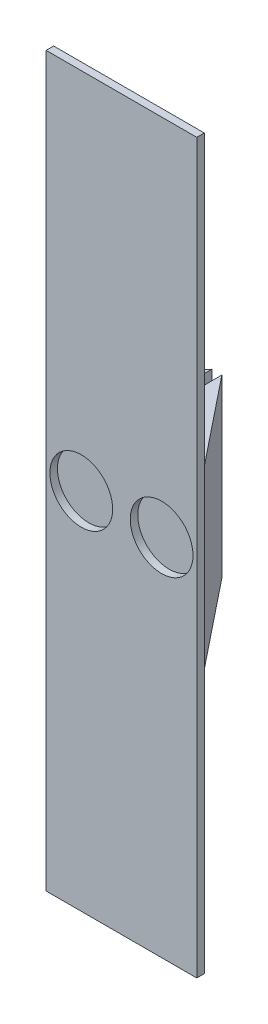
SolidWorks part; units mm, degrees
ref_plane "前视基准面" through (0, 0, 0) normal (0, 0, 1) x (1, 0, 0)
ref_plane "上视基准面" through (0, 0, 0) normal (0, 1, 0) x (1, 0, 0)
ref_plane "右视基准面" through (0, 0, 0) normal (1, 0, 0) x (0, 0, -1)
other "Configuration Table"
sketch "草图1" plane through (0, 0, 0) normal (0, 0, 1) x (1, 0, 0)
  line L1 (-15.6524, 41.5979) -> (44.3476, 41.5979)
  line L2 (-15.6524, 41.5979) -> (-15.6524, -18.4021)
  line L3 (-15.6524, -18.4021) -> (44.3476, -18.4021)
  line L4 (44.3476, 41.5979) -> (44.3476, -18.4021)
  dimension "D1" = 60
  dimension "D2" = 60
extrude "凸台-拉伸1" add sketch "草图1" along normal blind 3
sketch "草图2" plane through (0, 0, 0) normal (0, 0, -1) x (-1, 0, 0)
  line L0 (-44.3476, 41.5979) -> (-16.3476, 41.5979)
  line L1 (-44.3476, 41.5979) -> (15.6524, 41.5979) construction
  line L2 (-16.3476, 41.5979) -> (-16.3476, -18.4021)
  line L3 (15.6524, -18.4021) -> (-44.3476, -18.4021) construction
  line L4 (-16.3476, -18.4021) -> (-44.3476, -18.4021)
  line L5 (-44.3476, -18.4021) -> (-44.3476, 41.5979)
  line L6 (15.6524, 41.5979) -> (-12.3476, 41.5979)
  line L7 (-12.3476, 41.5979) -> (-12.3476, -18.4021)
  line L8 (-12.3476, -18.4021) -> (15.6524, -18.4021)
  line L9 (15.6524, -18.4021) -> (15.6524, 41.5979)
extrude "凸台-拉伸2" add sketch "草图2" along normal blind 35
sketch "草图3" plane through (0, 41.5979, 0) normal (0, 1, 0) x (1, 0, 0)
  line L0 (16.3476, 35) -> (44.3476, 0)
  line L1 (44.3476, -3) -> (44.3476, 35) construction
  line L2 (44.3476, 0) -> (44.3476, 35)
  line L3 (44.3476, 35) -> (16.3476, 35)
  line L5 (-15.6524, -3) -> (-15.6524, 35) construction
  line L7 (12.3476, 35) -> (-15.6524, 0)
  line L8 (-15.6524, 0) -> (-15.6524, 35)
  line L9 (-15.6524, 35) -> (12.3476, 35)
extrude "切除-拉伸1" cut sketch "草图3" against normal blind 60
sketch "草图4" plane through (0, 0, 3) normal (0, 0, 1) x (1, 0, 0)
  line L0 (-15.6524, 41.5979) -> (-14.1524, 41.5979)
  line L1 (44.3476, 41.5979) -> (-15.6524, 41.5979) construction
  line L2 (-14.1524, 41.5979) -> (10.8476, 41.5979)
  line L3 (10.8476, 41.5979) -> (10.8476, 11.5979)
  line L4 (10.8476, 11.5979) -> (-1.6524, 11.5979)
  line L5 (44.3476, 41.5979) -> (42.8476, 41.5979)
  line L6 (42.8476, 41.5979) -> (17.8476, 41.5979)
  line L7 (17.8476, 41.5979) -> (17.8476, 11.5979)
  line L8 (17.8476, 11.5979) -> (30.3476, 11.5979)
  circle A0 centre (-1.6524, 11.5979) radius 12.5
  circle A1 centre (30.3476, 11.5979) radius 12.5
extrude "切除-拉伸2" cut sketch "草图4" against normal blind 3
sketch "草图5" plane through (0, 41.5979, 0) normal (0, 1, 0) x (1, 0, 0)
  line L0 (12.3476, 35) -> (12.3476, 0)
  line L1 (12.3476, 0) -> (16.3476, 0)
  line L2 (16.3476, 0) -> (16.3476, 20)
  line L3 (16.3476, 35) -> (16.3476, 0) construction
  line L4 (16.3476, 20) -> (44.3476, 0)
  line L5 (44.3476, 0) -> (44.3476, -3)
  line L6 (44.3476, -3) -> (-15.6524, -3)
  line L7 (44.3476, -3) -> (-15.6524, -3) construction
  line L8 (-15.6524, -3) -> (-15.6524, 0)
  line L9 (-15.6524, 0) -> (12.3476, 35) construction
  line L10 (-15.6524, 0) -> (12.3476, 35)
extrude "凸台-拉伸3" add sketch "草图5" along normal blind 110
sketch "草图6" plane through (0, -18.4021, 0) normal (0, -1, 0) x (1, 0, 0)
  line L0 (-15.6524, 3) -> (-15.6524, 0)
  line L1 (-15.6524, 0) -> (12.3476, -35)
  line L2 (-15.6524, 0) -> (12.3476, -35) construction
  line L3 (12.3476, -35) -> (12.3476, 0)
  line L4 (12.3476, 0) -> (16.3476, 0)
  line L5 (16.3476, 0) -> (16.3476, -35)
  line L6 (16.3476, -35) -> (44.3476, 0)
  line L7 (16.3476, -35) -> (44.3476, 0) construction
  line L8 (44.3476, 0) -> (44.3476, 3)
  line L9 (44.3476, 3) -> (-15.6524, 3)
extrude "凸台-拉伸4" add sketch "草图6" along normal blind 110
sketch "草图7" plane through (0, -128.4021, 0) normal (0, -1, 0) x (1, 0, 0)
  line L0 (44.3476, 0) -> (16.3476, -35)
  line L1 (16.3476, 0) -> (16.3476, -35) construction
  line L2 (16.3476, -35) -> (44.3476, 0) construction
  line L3 (16.3476, -35) -> (16.3476, 0)
  line L4 (16.3476, 0) -> (44.3476, 0)
  line L5 (12.3476, -35) -> (-15.6524, 0)
  line L6 (-15.6524, 0) -> (12.3476, 0)
  line L7 (12.3476, -35) -> (12.3476, 0) construction
  line L8 (12.3476, 0) -> (12.3476, -35)
extrude "切除-拉伸3" cut sketch "草图7" against normal blind 100
sketch "草图9" plane through (0, 151.5979, 0) normal (0, 1, 0) x (1, 0, 0)
  line L0 (-15.6524, 0) -> (12.3476, 0)
  line L1 (12.3476, 0) -> (12.3476, 35)
  line L2 (12.3476, 35) -> (-15.6524, 0) construction
  line L3 (12.3476, 0) -> (12.3476, 35) construction
  line L4 (12.3476, 35) -> (-15.6524, 0)
  line L5 (16.3476, 0) -> (44.3476, 0)
  line L6 (44.3476, 0) -> (16.3476, 20) construction
  line L7 (44.3476, 0) -> (16.3476, 20) construction
  line L8 (44.3476, 0) -> (16.3476, 20)
  line L9 (16.3476, 20) -> (16.3476, 0)
extrude "切除-拉伸5" cut sketch "草图9" against normal blind 110
sketch "草图12" plane through (0, -128.4021, 0) normal (0, -1, 0) x (-1, 0, 0)
  line L1 (15.6524, -3) -> (-44.3476, -3)
  line L2 (15.6524, -3) -> (15.6524, 0)
  line L3 (15.6524, 0) -> (-44.3476, 0)
  line L4 (-44.3476, -3) -> (-44.3476, 0)
  line L6 (-44.3476, 0) -> (-44.3476, -3) construction
  line L7 (-44.3476, 0) -> (-16.3476, 0) construction
  dimension "D1" = 3
  dimension "D2" = 60
extrude "凸台-拉伸5" add sketch "草图12" along normal blind 5
sketch "草图13" plane through (0, 151.5979, 0) normal (0, 1, 0) x (1, 0, 0)
  line L1 (-15.6524, 0) -> (44.3476, 0)
  line L2 (-15.6524, 0) -> (-15.6524, -3)
  line L3 (-15.6524, -3) -> (44.3476, -3)
  line L4 (44.3476, 0) -> (44.3476, -3)
  dimension "D1" = 3
  dimension "D2" = 60
extrude "凸台-拉伸6" add sketch "草图13" along normal blind 5
